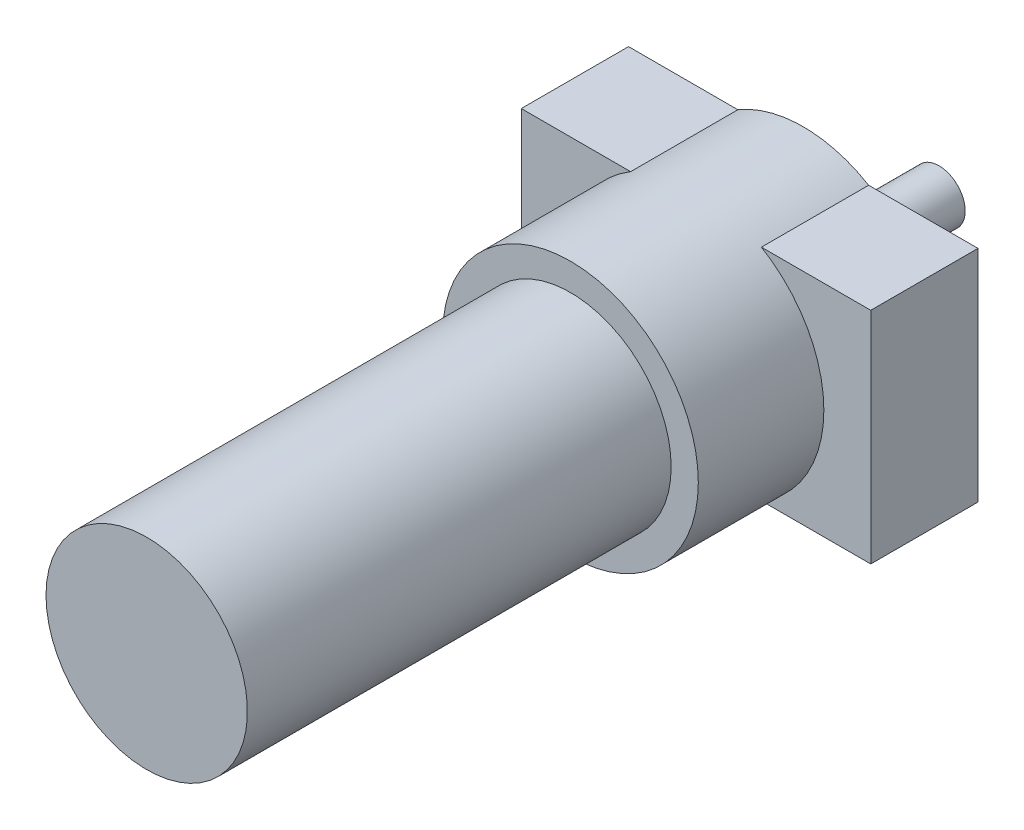
SolidWorks part; units mm, degrees
ref_plane "前视基准面" through (0, 0, 0) normal (0, 0, 1) x (1, 0, 0)
ref_plane "上视基准面" through (0, 0, 0) normal (0, 1, 0) x (1, 0, 0)
ref_plane "右视基准面" through (0, 0, 0) normal (1, 0, 0) x (0, 0, -1)
sketch "草图1" plane through (0, 0, 0) normal (0, 0, 1) x (1, 0, 0)
  circle A0 centre (0, 0) radius 10
  dimension "D1" = 20
extrude "凸台-拉伸1" add sketch "草图1" along normal blind 51.9
sketch "草图2" plane through (0, 0, 51.9) normal (0, 0, 1) x (1, 0, 0)
  line L1 (-25, -42) -> (25, -42) construction
  line L2 (-25, -42) -> (-25, 42) construction
  line L3 (-25, 42) -> (25, 42) construction
  line L4 (25, -42) -> (25, 42) construction
  line L5 (-25, -42) -> (25, 42) construction
  line L6 (-25, 42) -> (25, -42) construction
  circle A0 centre (0, 0) radius 48.8774
  point P0 (0, 0)
  dimension "D1" = 50
  dimension "D2" = 84
extrude "凸台-拉伸2" add sketch "草图2" along normal blind 89
sketch "草图4" plane through (0, 0, 51.9) normal (0, 0, -1) x (-1, 0, 0)
  line L1 (-66.8, -42) -> (66.8, -42)
  line L2 (-66.8, -42) -> (-66.8, 42)
  line L3 (-66.8, 42) -> (66.8, 42)
  line L4 (66.8, -42) -> (66.8, 42)
  line L5 (-66.8, -42) -> (66.8, 42) construction
  line L6 (-66.8, 42) -> (66.8, -42) construction
  point P0 (0, 0)
  dimension "D1" = 84
  dimension "D2" = 133.6
extrude "凸台-拉伸4" add sketch "草图4" against normal blind 41
sketch "草图5" plane through (0, 0, 51.9) normal (0, 0, -1) x (-1, 0, 0)
  circle A0 centre (0, 0) radius 38.5
  dimension "D1" = 77
extrude "凸台-拉伸5" add sketch "草图5" against normal blind 251
